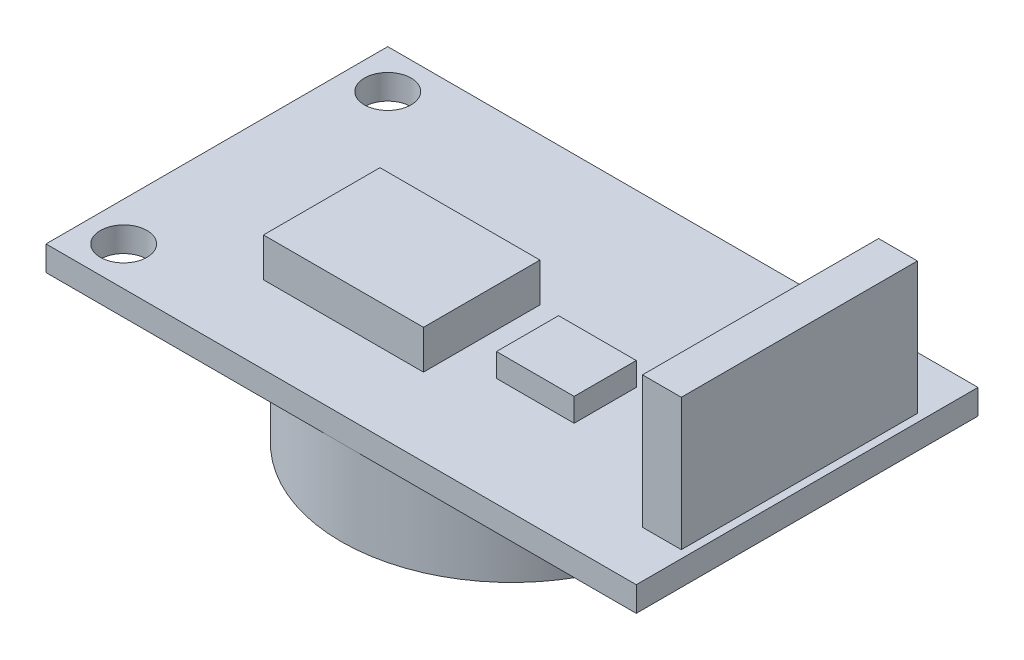
SolidWorks part; units mm, degrees
ref_plane "Front Plane" through (0, 0, 0) normal (0, 0, 1) x (1, 0, 0)
ref_plane "Top Plane" through (0, 0, 0) normal (0, 1, 0) x (1, 0, 0)
ref_plane "Right Plane" through (0, 0, 0) normal (1, 0, 0) x (0, 0, -1)
other "Configuration Table"
sketch "Sketch1" plane through (0, 0, 0) normal (0, 1, 0) x (1, 0, 0)
  line L1 (0, 0) -> (38, 0)
  line L2 (0, 0) -> (0, 22)
  line L3 (0, 22) -> (38, 22)
  line L4 (38, 0) -> (38, 22)
extrude "PCB" add sketch "Sketch1" along normal blind 1.6
sketch "Sketch2" plane through (0, 0, 0) normal (0, 1, 0) x (1, 0, 0)
  circle A0 centre (2.5, 19.5) radius 1.5
extrude "Mount_hole_1" cut sketch "Sketch2" against normal through all and the other way through all
sketch "Sketch3" plane through (0, 0, 0) normal (0, 1, 0) x (1, 0, 0)
  circle A0 centre (2.5, 2.5) radius 1.5
extrude "Mount_hole_2" cut sketch "Sketch3" against normal through all and the other way through all
sketch "Sketch4" plane through (0, 0, 0) normal (0, 1, 0) x (1, 0, 0)
  line L1 (9, 5) -> (19.3, 5)
  line L2 (9, 5) -> (9, 12.5)
  line L3 (9, 12.5) -> (19.3, 12.5)
  line L4 (19.3, 5) -> (19.3, 12.5)
extrude "DS3231_IC" add sketch "Sketch4" along normal blind 2.5 from offset 1.6
sketch "Sketch5" plane through (0, 0, 0) normal (0, 1, 0) x (1, 0, 0)
  line L1 (22, 7) -> (27, 7)
  line L2 (22, 7) -> (22, 11)
  line L3 (22, 11) -> (27, 11)
  line L4 (27, 7) -> (27, 11)
extrude "AT24C32_EEPROM" add sketch "Sketch5" along normal blind 1.5 from offset 1.6
sketch "Sketch6" plane through (0, 0, 0) normal (0, 1, 0) x (1, 0, 0)
  line L1 (35, 3.4) -> (37.5, 3.4)
  line L2 (35, 3.4) -> (35, 18.6)
  line L3 (35, 18.6) -> (37.5, 18.6)
  line L4 (37.5, 3.4) -> (37.5, 18.6)
extrude "Header_6pin" add sketch "Sketch6" along normal blind 8.5 from offset 1.6
sketch "Sketch7" plane through (0, 0, 0) normal (0, 1, 0) x (1, 0, 0)
  circle A0 centre (19, 11) radius 11
extrude "CR2032_holder" add sketch "Sketch7" against normal blind 5.5
